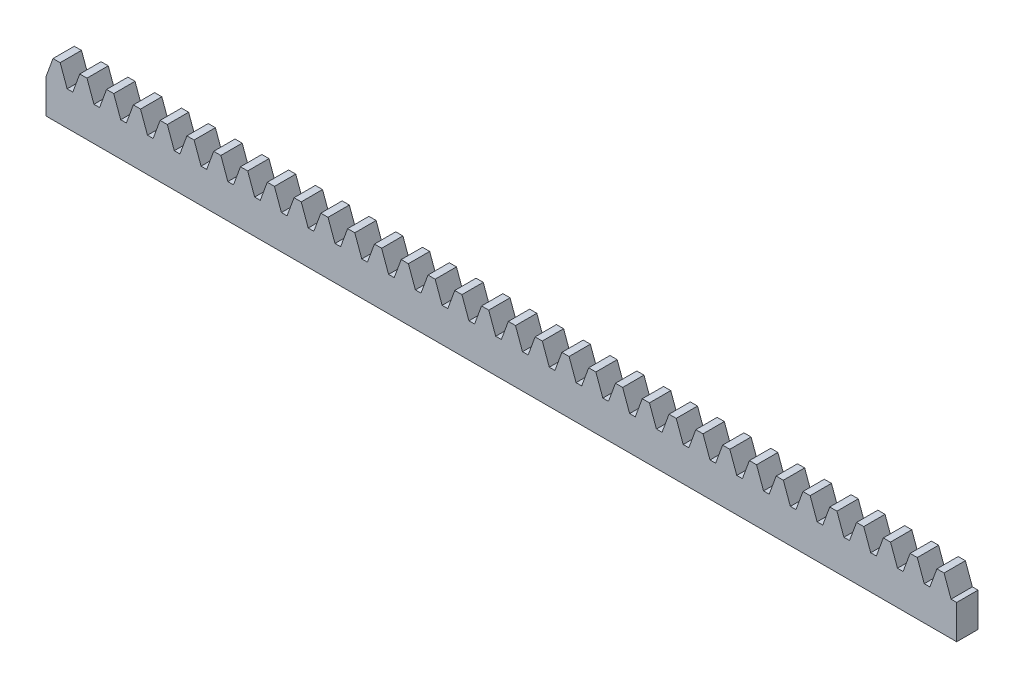
SolidWorks part; units mm, degrees
material "1.1193 (C45G)"
ref_plane "Front" through (0, 0, 0) normal (0, 0, 1) x (1, 0, 0)
ref_plane "Top" through (0, 0, 0) normal (0, 1, 0) x (1, 0, 0)
ref_plane "Right" through (0, 0, 0) normal (1, 0, 0) x (0, 0, -1)
sketch "Sketch1" plane through (0, 0, 0) normal (0, 0, 1) x (1, 0, 0)
  line L1 (0, 0) -> (213.6283, 0)
  line L2 (0, 0) -> (0, -8)
  line L3 (0, -8) -> (213.6283, -8)
  line L4 (213.6283, 0) -> (213.6283, -8)
  dimension "D1" = 8
  dimension "L" = 213.6283
extrude "Extrude1" add sketch "Sketch1" along normal blind 5
sketch "Sketch2" plane through (0, 0, 5) normal (0, 0, 1) x (1, 0, 0)
  line L0 (0, 0) -> (1.6379, 4.5)
  line L1 (1.6379, 4.5) -> (3.3236, 4.5)
  line L2 (3.3236, 4.5) -> (4.9614, 0)
  line L3 (213.6283, 0) -> (0, 0) construction
  line L4 (0, 0) -> (4.9614, 0)
  line L5 (0.9099, 2.5) -> (4.0515, 2.5) construction
  dimension "alpha2" = 70
  dimension "alpha" = 110
  dimension "ha" = 2
  dimension "hf" = 2.5
  dimension "S" = 3.1416
extrude "Extrude2" add sketch "Sketch2" against normal up to surface (5 mm away) up to face at (106.8142, -4, 0)
pattern_linear "LPattern1" count 34 spacing 6.2832 along (1, 0, 0) of "Extrude2"
